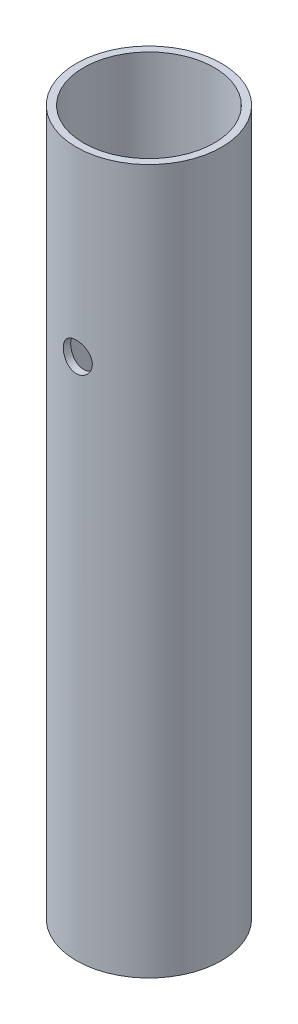
SolidWorks part; units mm, degrees
material "ABS"
ref_plane "Front Plane" through (0, 0, 0) normal (0, 0, 1) x (1, 0, 0)
ref_plane "Top Plane" through (0, 0, 0) normal (0, 1, 0) x (1, 0, 0)
ref_plane "Right Plane" through (0, 0, 0) normal (1, 0, 0) x (0, 0, -1)
sketch "Sketch2" plane through (0, 0, 0) normal (0, 1, 0) x (1, 0, 0)
  circle A0 centre (0, 0) radius 31.75
  circle A1 centre (0, 0) radius 28.575
  dimension "D1" = 63.5
  dimension "D2" = 3.175
extrude "Boss-Extrude1" add sketch "Sketch2" along normal blind 307.975
sketch "Sketch3" plane through (0, 0, 0) normal (0, 0, 1) x (1, 0, 0)
  circle A0 centre (0, 228.6) radius 6.35
  point P2 (0, 228.6)
  point P3 (0, 0)
  dimension "D2" = 12.7
  dimension "D1" = 228.6
extrude "Cut-Extrude1" cut sketch "Sketch3" against normal through all both and the other way through all
